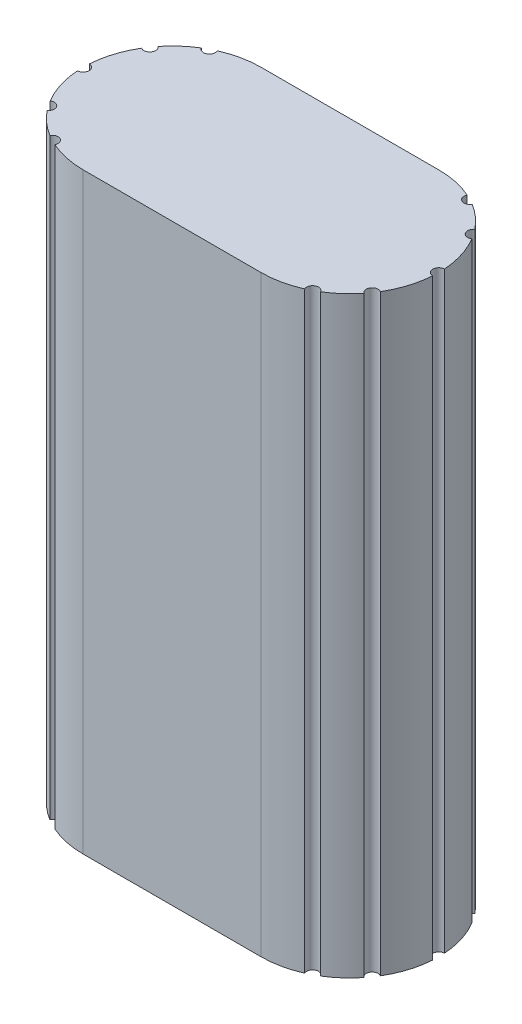
SolidWorks part; units mm, degrees
ref_plane "Front Plane" through (0, 0, 0) normal (0, 0, 1) x (1, 0, 0)
ref_plane "Top Plane" through (0, 0, 0) normal (0, 1, 0) x (1, 0, 0)
ref_plane "Right Plane" through (0, 0, 0) normal (1, 0, 0) x (0, 0, -1)
sketch "Sketch1" plane through (0, 0, 0) normal (0, 1, 0) x (1, 0, 0)
  line L0 (15, 0) -> (-15, 0) construction
  line L1 (15, -15) -> (-15, -15)
  line L2 (15, 15) -> (-15, 15)
  arc A0 (15, -15) -> (15, 15) centre (15, 0) ccw
  arc A1 (-15, 15) -> (-15, -15) centre (-15, 0) ccw
  point P2 (0, 0)
  dimension "D1" = 30
  dimension "D2" = 30
extrude "Boss-Extrude1" add sketch "Sketch1" along normal blind 100
sketch "Sketch2" plane through (0, 100, 0) normal (0, 1, 0) x (1, 0, 0)
  line L0 (0, 15) -> (0, -15) construction
  line L1 (15, 15) -> (-15, 15) construction
  line L2 (-15, -15) -> (15, -15) construction
  line L3 (-15, 15) -> (-15, -15) construction
  line L4 (-15, 0) -> (-21.9823, 13.2758) construction
  line L5 (-21.9823, 13.2758) -> (-21.9823, -13.2758) construction
  line L6 (-21.9823, -13.2758) -> (-15, 0) construction
  line L7 (-15, 0) -> (-30, 0) construction
  line L8 (-15, 0) -> (-27.322, 8.5539) construction
  arc A0 (-15, 15) -> (-15, -15) centre (-15, 0) ccw construction
  circle A1 centre (-21.9823, 13.2758) radius 1
  circle A2 centre (-30, 0) radius 1
  circle A3 centre (-21.9823, -13.2758) radius 1
  circle A4 centre (-27.322, 8.5539) radius 1
  circle A5 centre (-27.322, -8.5539) radius 1
  circle A6 centre (21.9823, -13.2758) radius 1
  circle A7 centre (27.322, -8.5539) radius 1
  circle A8 centre (30, 0) radius 1
  circle A9 centre (27.322, 8.5539) radius 1
  circle A10 centre (21.9823, 13.2758) radius 1
  dimension "D1" = 2
  dimension "D2" = 21.9823
  dimension "D3" = 27.49
extrude "Cut-Extrude1" cut sketch "Sketch2" against normal through all
